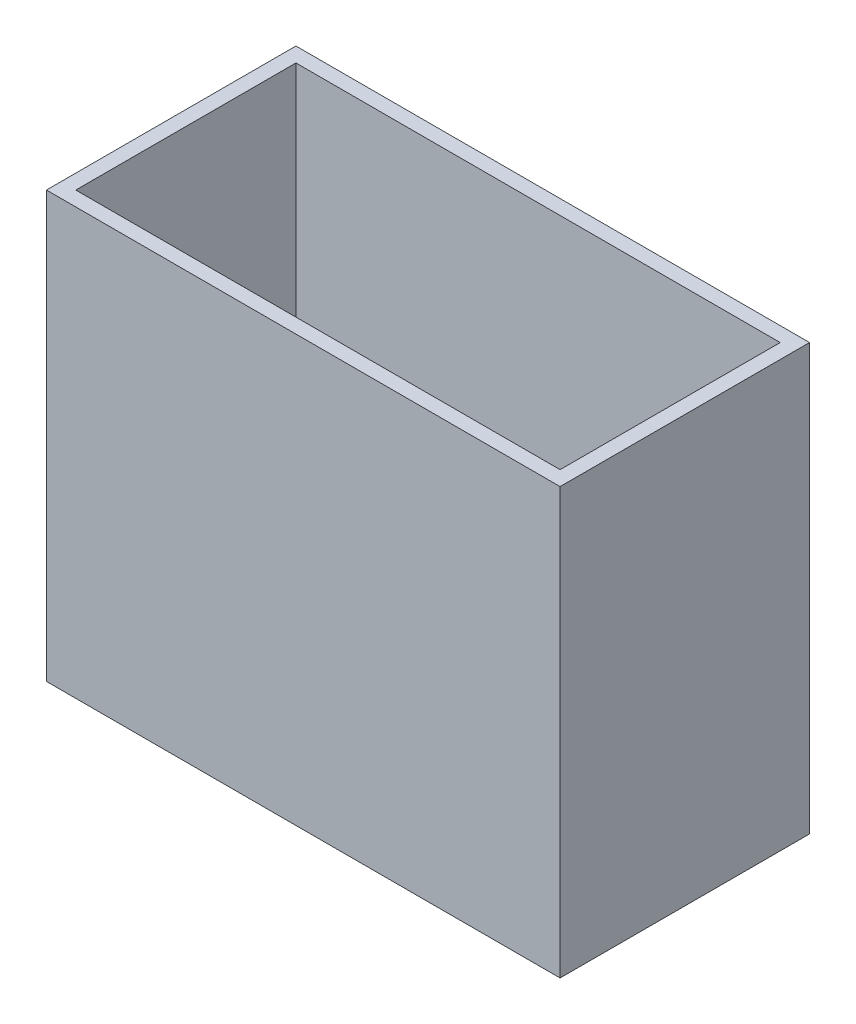
SolidWorks part; units mm, degrees
ref_plane "Front Plane" through (0, 0, 0) normal (0, 0, 1) x (1, 0, 0)
ref_plane "Top Plane" through (0, 0, 0) normal (0, 1, 0) x (1, 0, 0)
ref_plane "Right Plane" through (0, 0, 0) normal (1, 0, 0) x (0, 0, -1)
sketch "Sketch1" plane through (0, 0, 0) normal (0, 1, 0) x (1, 0, 0)
  line L1 (0, 0) -> (-70, 0)
  line L2 (0, 0) -> (0, -34)
  line L3 (0, -34) -> (-70, -34)
  line L4 (-70, 0) -> (-70, -34)
  dimension "D1" = 70
  dimension "D2" = 34
extrude "Boss-Extrude2" add sketch "Sketch1" along normal blind 58
sketch "Sketch4" plane through (0, 58, 0) normal (0, 1, 0) x (1, 0, 0)
  line L0 (0, 0) -> (-70, 0) construction
  line L1 (-68, -2) -> (-2, -2)
  line L2 (-68, -2) -> (-68, -32)
  line L3 (-68, -32) -> (-2, -32)
  line L4 (-2, -2) -> (-2, -32)
  line L5 (-70, -34) -> (0, -34) construction
  line L6 (0, -34) -> (0, 0) construction
  line L7 (-70, 0) -> (-70, -34) construction
  dimension "D1" = 2
  dimension "D2" = 2
  dimension "D3" = 2
  dimension "D4" = 2
extrude "Cut-Extrude1" cut sketch "Sketch4" against normal blind 56
sketch "Sketch5" plane through (0, 2, 0) normal (0, 1, 0) x (1, 0, 0)
  line L0 (-2, -2) -> (-68, -2) construction
  line L1 (-56, -7) -> (-32, -7)
  line L2 (-56, -7) -> (-56, -27)
  line L3 (-56, -27) -> (-32, -27)
  line L4 (-32, -7) -> (-32, -27)
  line L5 (-68, -32) -> (-2, -32) construction
  line L6 (-68, -2) -> (-68, -32) construction
  line L7 (-2, -32) -> (-2, -2) construction
  dimension "D1" = 5
  dimension "D2" = 5
  dimension "D3" = 12
  dimension "D4" = 30
extrude "Cut-Extrude2" cut sketch "Sketch5" against normal blind 2
